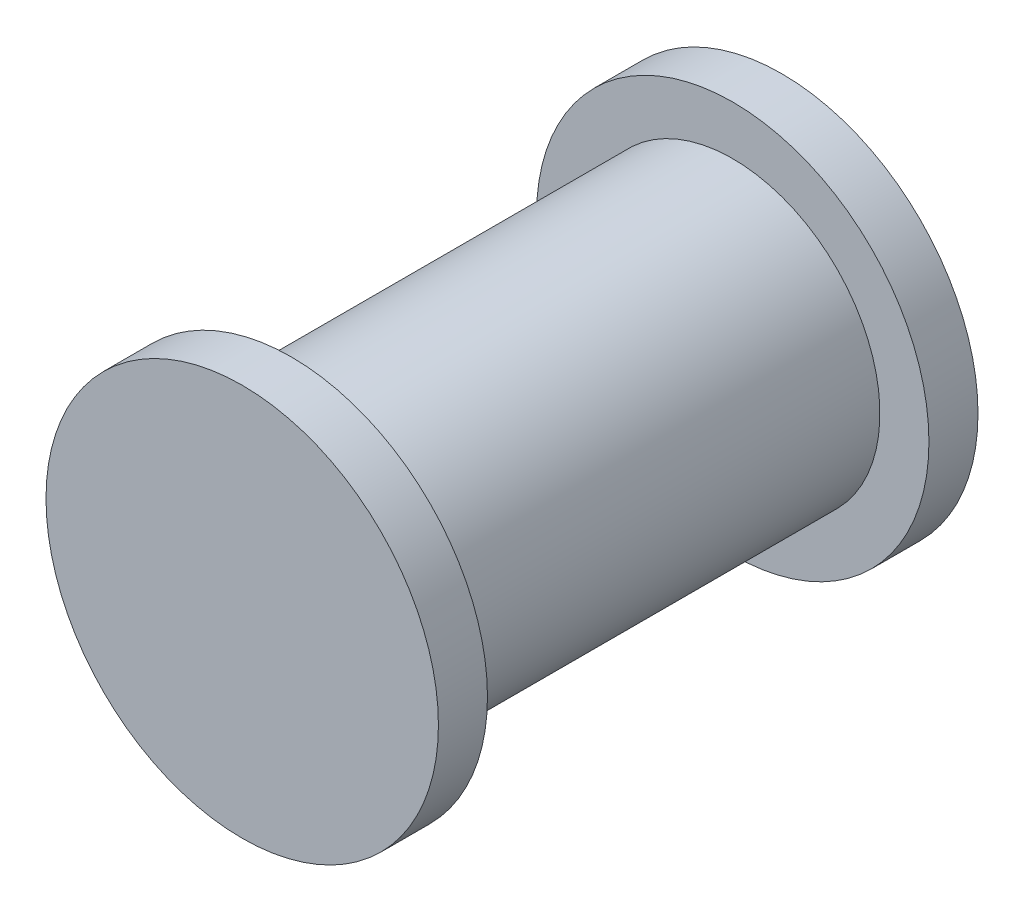
SolidWorks part; units mm, degrees
ref_plane "前视基准面" through (0, 0, 0) normal (0, 0, 1) x (1, 0, 0)
ref_plane "上视基准面" through (0, 0, 0) normal (0, 1, 0) x (1, 0, 0)
ref_plane "右视基准面" through (0, 0, 0) normal (1, 0, 0) x (0, 0, -1)
sketch "草图1" plane through (0, 0, 0) normal (0, 0, 1) x (1, 0, 0)
  circle A0 centre (0, 0) radius 30
extrude "凸台-拉伸1" add sketch "草图1" along normal blind 90
sketch "草图2" plane through (0, 0, 90) normal (0, 0, 1) x (1, 0, 0)
  circle A0 centre (0, 0) radius 40
  dimension "D1" = 80
extrude "凸台-拉伸2" add sketch "草图2" along normal blind 10
sketch "草图3" plane through (0, 0, 0) normal (0, 0, -1) x (-1, 0, 0)
  circle A0 centre (0, 0) radius 40
extrude "凸台-拉伸3" add sketch "草图3" along normal blind 10
scale "缩放比例1" scale about origin uniform scaling yes scale factor 0.345
